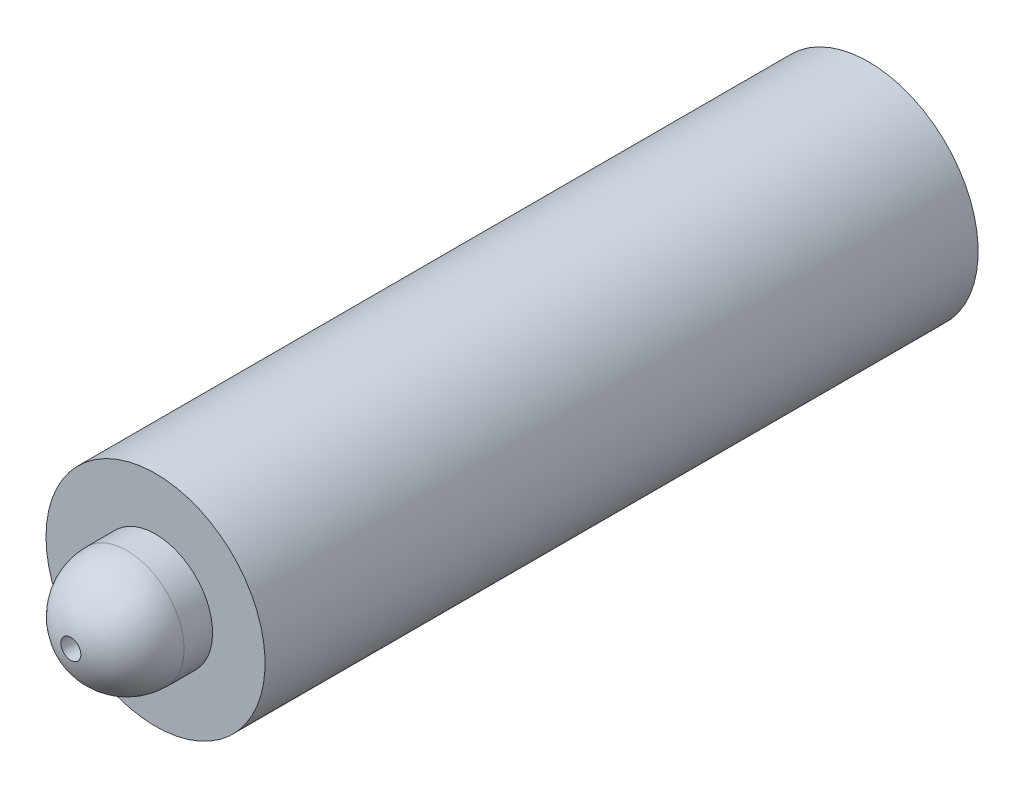
SolidWorks part; units mm, degrees
material "PLA"
ref_plane "Front Plane" through (0, 0, 0) normal (0, 0, 1) x (1, 0, 0)
ref_plane "Top Plane" through (0, 0, 0) normal (0, 1, 0) x (1, 0, 0)
ref_plane "Right Plane" through (0, 0, 0) normal (1, 0, 0) x (0, 0, -1)
sketch "Sketch1" plane through (0, 0, 0) normal (0, 0, 1) x (1, 0, 0)
  circle A0 centre (0, 0) radius 12.192
  circle A1 centre (0, 0) radius 9.017
  dimension "D1" = 24.384
  dimension "D2" = 3.175
extrude "Core Extrude" add sketch "Sketch1" along normal blind 79.375
ref_plane "BreakAway Plane" through (0, 0, 36.195) normal (0, 0, 1) x (1, 0, 0)
sketch "Sketch2" plane through (0, 0, 0) normal (0, 0, -1) x (-1, 0, 0)
  line L1 (0, 10.922) -> (0, -10.922) construction
  line L6 (8.4395, 3.175) -> (8.4395, -3.175)
  line L7 (3.175, -8.4395) -> (-3.175, -8.4395)
  line L8 (-8.4395, -3.175) -> (-8.4395, 3.175)
  line L9 (-3.175, 8.4395) -> (3.175, 8.4395)
  circle A3 centre (0, 0) radius 9.017 construction
  circle A6 centre (0, 0) radius 12.192
  circle A7 centre (0, 0) radius 12.192
  circle A8 centre (0, 0) radius 9.017
  circle A11 centre (0, 0) radius 10.922 construction
  arc A12 (8.4395, 3.175) -> (8.4395, -3.175) centre (7.6504, 0) cw
  arc A13 (3.175, -8.4395) -> (-3.175, -8.4395) centre (0, -7.6504) cw
  arc A14 (-8.4395, -3.175) -> (-8.4395, 3.175) centre (-7.6504, 0) cw
  arc A15 (-3.175, 8.4395) -> (3.175, 8.4395) centre (0, 7.6504) cw
  point P24 (0, 0)
  point P27 (-0.2677, -0.2677)
  circle M6 centre (0, 0) radius 9.017
  dimension "D3" = 21.844
  dimension "D1" = 0
  dimension "D2" = 6.35
extrude "Groove Cut" cut sketch "Sketch2" against normal blind 19.05 contours A14 M6 | A15 M6 | A12 M6 | A13 M6
sketch "Sketch3" plane through (0, 0, 79.375) normal (0, 0, 1) x (1, 0, 0)
  circle A0 centre (0, 0) radius 9.017
  circle A1 centre (0, 0) radius 9.017 construction
  circle A2 centre (0, 0) radius 9.017
  circle M2 centre (0, 0) radius 9.017
extrude "Bumpy Extrude" add sketch "Sketch3" against normal blind 3.175 contours M2
sketch "Sketch5" plane through (0, 0, 0) normal (1, 0, 0) x (0, 0, -1)
  line L0 (-79.375, 0) -> (-88.9, 0)
  line L1 (-79.375, 12.192) -> (-79.375, -12.192) construction
  line L3 (-79.375, 6.35) -> (-82.55, 6.35)
  line L4 (-79.375, 6.35) -> (-79.375, 0)
  arc A1 (-82.55, 6.35) -> (-88.9, 0) centre (-82.55, 0) ccw
  dimension "D3" = 6.35
  dimension "D1" = 3.175
  dimension "D2" = 9.525
revolve "Revolve1" add sketch "Sketch5" angle 360 about L0
sketch "Sketch7" plane through (0, 0, 76.2) normal (0, 0, -1) x (-1, 0, 0)
  circle A0 centre (0, 0) radius 1.1112
  dimension "D1" = 2.2225
extrude "Cut-Extrude3" cut sketch "Sketch7" against normal through all
